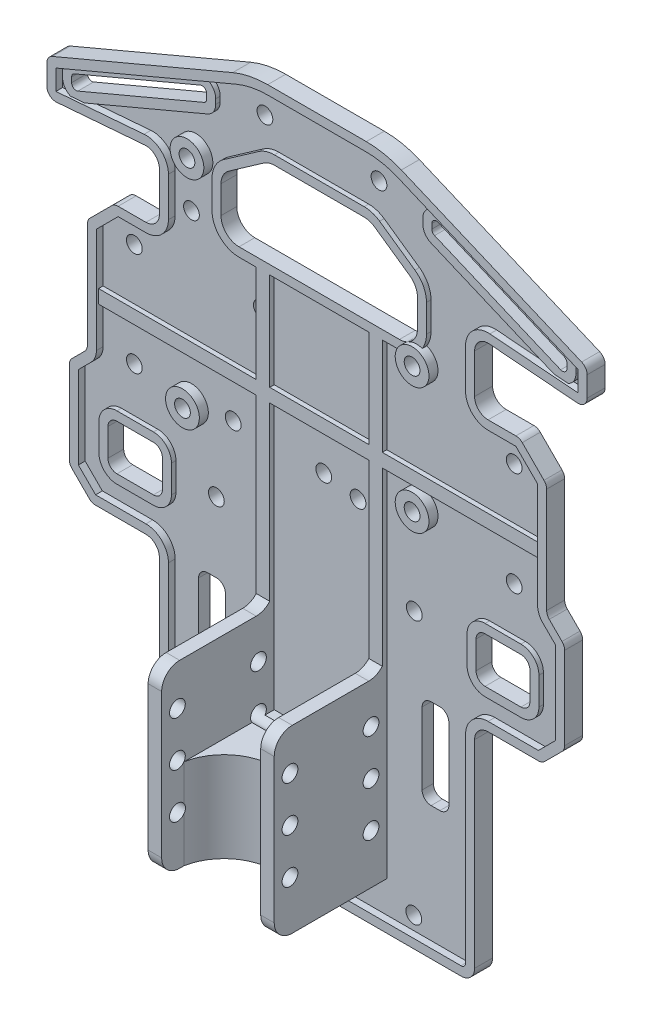
SolidWorks part; units mm, degrees
ref_plane "Front Plane" through (0, 0, 0) normal (0, 0, 1) x (1, 0, 0)
ref_plane "Top Plane" through (0, 0, 0) normal (0, 1, 0) x (1, 0, 0)
ref_plane "Right Plane" through (0, 0, 0) normal (1, 0, 0) x (0, 0, -1)
sketch "Sketch1" plane through (0, 0, 0) normal (0, 0, 1) x (1, 0, 0)
  line L1 (-55, 30) -> (-35, 30) construction
  line L2 (-55, 30) -> (-55, -30) construction
  line L3 (-55, -30) -> (-35, -30) construction
  line L4 (55, 30) -> (55, -30) construction
  line L5 (-55, 30) -> (55, -30) construction
  line L6 (-55, -30) -> (55, 30) construction
  line L8 (-35, 41.7504) -> (-35, 33)
  line L10 (35, 41.7504) -> (35, 33)
  line L11 (-35, 45) -> (35, 30) construction
  line L12 (-35, 30) -> (35, 45) construction
  line L13 (-60, 70) -> (60, 70) construction
  line L14 (-60, 70) -> (-60, 45) construction
  line L15 (-60, 45) -> (-35, 45) construction
  line L16 (60, 70) -> (60, 45) construction
  line L17 (-60, 70) -> (60, 45) construction
  line L18 (-60, 45) -> (60, 70) construction
  line L20 (0, 57.5) -> (0, 37.5) construction
  line L21 (32, -80) -> (-32, -80)
  line L22 (35, -77) -> (35, -33)
  line L24 (-35, -77) -> (-35, -33)
  line L25 (35, -80) -> (-35, -30) construction
  line L26 (35, -30) -> (-35, -80) construction
  line L27 (0, 37.5) -> (0, 0) construction
  line L28 (0, 0) -> (0, -55) construction
  line L29 (35, 45) -> (60, 45) construction
  line L30 (35, 30) -> (55, 30) construction
  line L31 (35, -30) -> (55, -30) construction
  line L32 (-35, -30) -> (35, -30) construction
  line L33 (35, 30) -> (-35, 30) construction
  line L34 (-35, 45) -> (35, 45) construction
  line L35 (-60, 45.1664) -> (-60, 49.6735)
  line L36 (-58.7779, 51.516) -> (-18.7303, 68.425)
  line L37 (-10.9508, 70) -> (10.9508, 70)
  line L38 (18.7303, 68.425) -> (58.7779, 51.516)
  line L39 (60, 49.6735) -> (60, 45.1664)
  line L40 (57.8405, 43.1728) -> (38.2392, 44.7409)
  line L41 (-38.2392, 44.7409) -> (-57.8405, 43.1728)
  line L42 (-60, 51) -> (60, 51) construction
  line L43 (60, 43) -> (-60, 43) construction
  line L44 (0, 57.5) -> (0, 70) construction
  line L45 (-38, -30) -> (-49.1716, -30)
  line L46 (-50.5858, -29.4142) -> (-54.4142, -25.5858)
  line L47 (-55, -24.1716) -> (-55, -5.8284)
  line L48 (-54.4142, -4.4142) -> (-51.5858, -1.5858)
  line L49 (-51, -0.1716) -> (-51, 23.1716)
  line L50 (-50.4142, 24.5858) -> (-45.5858, 29.4142)
  line L51 (-44.1716, 30) -> (-38, 30)
  line L52 (0, -55) -> (0, 55) construction
  line L53 (44.1716, 30) -> (38, 30)
  line L54 (50.4142, 24.5858) -> (45.5858, 29.4142)
  line L55 (51, -0.1716) -> (51, 23.1716)
  line L56 (54.4142, -4.4142) -> (51.5858, -1.5858)
  line L57 (55, -24.1716) -> (55, -5.8284)
  line L58 (50.5858, -29.4142) -> (54.4142, -25.5858)
  line L59 (38, -30) -> (49.1716, -30)
  line L60 (-55, 0) -> (55, 0) construction
  arc A0 (60, 45.1664) -> (57.8405, 43.1728) centre (58, 45.1664) cw
  arc A1 (58.7779, 51.516) -> (60, 49.6735) centre (58, 49.6735) cw
  arc A2 (-60, 45.1664) -> (-57.8405, 43.1728) centre (-58, 45.1664) ccw
  arc A3 (-60, 49.6735) -> (-58.7779, 51.516) centre (-58, 49.6735) cw
  arc A4 (10.9508, 70) -> (18.7303, 68.425) centre (10.9508, 50) cw
  arc A5 (-18.7303, 68.425) -> (-10.9508, 70) centre (-10.9508, 50) cw
  arc A6 (-45.5858, 29.4142) -> (-44.1716, 30) centre (-44.1716, 28) cw
  arc A7 (-51, 23.1716) -> (-50.4142, 24.5858) centre (-49, 23.1716) cw
  arc A8 (-51.5858, -1.5858) -> (-51, -0.1716) centre (-53, -0.1716) ccw
  arc A9 (-55, -5.8284) -> (-54.4142, -4.4142) centre (-53, -5.8284) cw
  arc A10 (-54.4142, -25.5858) -> (-55, -24.1716) centre (-53, -24.1716) cw
  arc A11 (-49.1716, -30) -> (-50.5858, -29.4142) centre (-49.1716, -28) cw
  arc A12 (45.5858, 29.4142) -> (44.1716, 30) centre (44.1716, 28) ccw
  arc A13 (51, 23.1716) -> (50.4142, 24.5858) centre (49, 23.1716) ccw
  arc A14 (51.5858, -1.5858) -> (51, -0.1716) centre (53, -0.1716) cw
  arc A15 (55, -5.8284) -> (54.4142, -4.4142) centre (53, -5.8284) ccw
  arc A16 (54.4142, -25.5858) -> (55, -24.1716) centre (53, -24.1716) ccw
  arc A17 (49.1716, -30) -> (50.5858, -29.4142) centre (49.1716, -28) ccw
  arc A18 (32, -80) -> (35, -77) centre (32, -77) ccw
  arc A19 (-32, -80) -> (-35, -77) centre (-32, -77) cw
  arc A20 (38.2392, 44.7409) -> (35, 41.7504) centre (38, 41.7504) ccw
  arc A21 (38, 30) -> (35, 33) centre (38, 33) cw
  arc A22 (-35, 33) -> (-38, 30) centre (-38, 33) cw
  arc A23 (-38.2392, 44.7409) -> (-35, 41.7504) centre (-38, 41.7504) cw
  arc A24 (35, -33) -> (38, -30) centre (38, -33) cw
  arc A25 (-38, -30) -> (-35, -33) centre (-38, -33) cw
  point P0 (0, 0)
  point P6 (0, 37.5)
  point P11 (0, 57.5)
  point P16 (0, -55)
  point P46 (15, 70)
  point P49 (-15, 70)
  point P58 (-45, 30)
  point P61 (-51, 24)
  point P64 (-51, -1)
  point P67 (-55, -5)
  point P70 (-55, -25)
  point P73 (-50, -30)
  dimension "D11" = 2
  dimension "D12" = 20
  dimension "D20" = 2
  dimension "D21" = 3
  dimension "D1" = 120
  dimension "D2" = 25
  dimension "D3" = 15
  dimension "D4" = 60
  dimension "D5" = 50
  dimension "D6" = 70
  dimension "D7" = 70
  dimension "D8" = 2
  dimension "D9" = 8
  dimension "D10" = 30
  dimension "D13" = 15
  dimension "D14" = 45
  dimension "D15" = 20
  dimension "D16" = 45
  dimension "D17" = 45
  dimension "D18" = 25
  dimension "D19" = 4
  dimension "D22" = 110
extrude "Boss-Extrude1" add sketch "Sketch1" along normal blind 2.5
sketch "Sketch14" plane through (0, 0, 2.5) normal (0, 0, 1) x (1, 0, 0)
  line L0 (-53.611, 47.1847) -> (-25.611, 59.0069)
  line L1 (-25, 59.9281) -> (-25, 61.0136)
  line L2 (-26.389, 61.9349) -> (-54.389, 50.1127)
  line L3 (-55, 49.1914) -> (-55, 48.1059)
  line L4 (-18.7303, 68.425) -> (-58.7779, 51.516) construction
  line L5 (0, -55) -> (0, 55) construction
  line L6 (55, 49.1914) -> (55, 48.1059)
  line L7 (26.389, 61.9349) -> (54.389, 50.1127)
  line L8 (25, 59.9281) -> (25, 61.0136)
  line L9 (53.611, 47.1847) -> (25.611, 59.0069)
  arc A0 (-25.611, 59.0069) -> (-25, 59.9281) centre (-26, 59.9281) ccw
  arc A1 (-25, 61.0136) -> (-26.389, 61.9349) centre (-26, 61.0136) ccw
  arc A2 (-53.611, 47.1847) -> (-55, 48.1059) centre (-54, 48.1059) cw
  arc A3 (-54.389, 50.1127) -> (-55, 49.1914) centre (-54, 49.1914) ccw
  arc A4 (54.389, 50.1127) -> (55, 49.1914) centre (54, 49.1914) cw
  arc A5 (53.611, 47.1847) -> (55, 48.1059) centre (54, 48.1059) ccw
  arc A6 (25, 61.0136) -> (26.389, 61.9349) centre (26, 61.0136) cw
  arc A7 (25.611, 59.0069) -> (25, 59.9281) centre (26, 59.9281) cw
  point P14 (-25, 60.4709)
  dimension "D1" = 1
  dimension "D2" = 3
  dimension "D3" = 30
  dimension "D4" = 3
  dimension "D5" = 25
extrude "Cut-Extrude6" cut sketch "Sketch14" against normal through all
sketch "Sketch17" plane through (0, 0, 2.5) normal (0, 0, 1) x (1, 0, 0)
  line L0 (21.6202, 4.389) -> (21.6202, 32.389) construction
  line L1 (-29.3798, 35.789) -> (-29.3798, -1.211) construction
  line L2 (-29.3798, -1.211) -> (7.6202, -1.211) construction
  line L3 (7.6202, -1.211) -> (7.6202, 35.789) construction
  line L4 (7.6202, 35.789) -> (-29.3798, 35.789) construction
  line L6 (24.6202, 4.389) -> (21.6202, 4.389) construction
  circle A0 centre (21.6202, 32.389) radius 1.75
  circle A1 centre (21.6202, 4.389) radius 1.75
  circle A2 centre (-29.3798, -1.211) radius 1.75
  circle A3 centre (-28.3798, 47.389) radius 1.75
  circle A4 centre (-29.3798, 35.789) radius 1.75
  circle A6 centre (7.6202, -1.211) radius 1.75
  dimension "D1" = 3.5
  dimension "D2" = 3.5
  dimension "D3" = 3.5
  dimension "D6" = 3.5
  dimension "D8" = 3.5
  dimension "D4" = 37
  dimension "D5" = 37
  dimension "D10" = 3
  dimension "D11" = 28
  dimension "D12" = 15
  dimension "D13" = 5.6
  dimension "D14" = 50
  dimension "D15" = 51
extrude "Cut-Extrude8" cut sketch "Sketch17" against normal through all both and the other way through all
ref_plane "Plane1" through (-35, -33, 2.5) normal (0, -1, 0) x (-1, 0, 0)
sketch "Sketch19" plane through (0, 0, 2.5) normal (0, 0, 1) x (1, 0, 0)
  line L0 (58, 45.1664) -> (58, 49.6735)
  line L1 (58, 49.6735) -> (17.9523, 66.5825)
  line L2 (10.9508, 68) -> (-10.9508, 68)
  line L3 (-17.9523, 66.5825) -> (-58, 49.6735)
  line L4 (-58, 49.6735) -> (-58, 45.1664)
  line L5 (-58, 45.1664) -> (-38.3987, 46.7345)
  line L6 (-33, 41.7504) -> (-33, 33)
  line L7 (-38, 28) -> (-44.1716, 28)
  line L8 (-44.1716, 28) -> (-49, 23.1716)
  line L9 (-49, 23.1716) -> (-49, -0.1716)
  line L10 (-50.1716, -3) -> (-53, -5.8284)
  line L11 (-53, -5.8284) -> (-53, -24.1716)
  line L12 (-53, -24.1716) -> (-49.1716, -28)
  line L13 (-49.1716, -28) -> (-38, -28)
  line L14 (-33, -33) -> (-33, -77)
  line L15 (-32, -78) -> (32, -78)
  line L16 (33, -77) -> (33, -33)
  line L17 (38, -28) -> (49.1716, -28)
  line L18 (49.1716, -28) -> (53, -24.1716)
  line L19 (53, -24.1716) -> (53, -5.8284)
  line L20 (53, -5.8284) -> (50.1716, -3)
  line L21 (49, -0.1716) -> (49, 23.1716)
  line L22 (49, 23.1716) -> (44.1716, 28)
  line L23 (44.1716, 28) -> (38, 28)
  line L24 (33, 33) -> (33, 41.7504)
  line L25 (38.3987, 46.7345) -> (58, 45.1664)
  line L26 (60, 45.1664) -> (60, 49.6735)
  line L27 (58.7779, 51.516) -> (18.7303, 68.425)
  line L28 (10.9508, 70) -> (-10.9508, 70)
  line L29 (-18.7303, 68.425) -> (-58.7779, 51.516)
  line L30 (-60, 49.6735) -> (-60, 45.1664)
  line L31 (-57.8405, 43.1728) -> (-38.2392, 44.7409)
  line L32 (-35, 41.7504) -> (-35, 33)
  line L33 (-38, 30) -> (-44.1716, 30)
  line L34 (-45.5858, 29.4142) -> (-50.4142, 24.5858)
  line L35 (-51, 23.1716) -> (-51, -0.1716)
  line L36 (-51.5858, -1.5858) -> (-54.4142, -4.4142)
  line L37 (-55, -5.8284) -> (-55, -24.1716)
  line L38 (-54.4142, -25.5858) -> (-50.5858, -29.4142)
  line L39 (-49.1716, -30) -> (-38, -30)
  line L40 (-35, -33) -> (-35, -77)
  line L41 (-32, -80) -> (32, -80)
  line L42 (35, -77) -> (35, -33)
  line L43 (38, -30) -> (49.1716, -30)
  line L44 (50.5858, -29.4142) -> (54.4142, -25.5858)
  line L45 (55, -24.1716) -> (55, -5.8284)
  line L46 (54.4142, -4.4142) -> (51.5858, -1.5858)
  line L47 (51, -0.1716) -> (51, 23.1716)
  line L48 (50.4142, 24.5858) -> (45.5858, 29.4142)
  line L49 (44.1716, 30) -> (38, 30)
  line L50 (35, 33) -> (35, 41.7504)
  line L51 (38.2392, 44.7409) -> (57.8405, 43.1728)
  line L52 (60, 45.1664) -> (60, 49.6735)
  line L53 (58.7779, 51.516) -> (18.7303, 68.425)
  line L54 (10.9508, 70) -> (-10.9508, 70)
  line L55 (-18.7303, 68.425) -> (-58.7779, 51.516)
  line L56 (-60, 49.6735) -> (-60, 45.1664)
  line L57 (-57.8405, 43.1728) -> (-38.2392, 44.7409)
  line L58 (-35, 41.7504) -> (-35, 33)
  line L59 (-38, 30) -> (-44.1716, 30)
  line L60 (-45.5858, 29.4142) -> (-50.4142, 24.5858)
  line L61 (-51, 23.1716) -> (-51, -0.1716)
  line L62 (-51.5858, -1.5858) -> (-54.4142, -4.4142)
  line L63 (-55, -5.8284) -> (-55, -24.1716)
  line L64 (-54.4142, -25.5858) -> (-50.5858, -29.4142)
  line L65 (-49.1716, -30) -> (-38, -30)
  line L66 (-35, -33) -> (-35, -77)
  line L67 (-32, -80) -> (32, -80)
  line L68 (35, -77) -> (35, -33)
  line L69 (38, -30) -> (49.1716, -30)
  line L70 (50.5858, -29.4142) -> (54.4142, -25.5858)
  line L71 (55, -24.1716) -> (55, -5.8284)
  line L72 (54.4142, -4.4142) -> (51.5858, -1.5858)
  line L73 (51, -0.1716) -> (51, 23.1716)
  line L74 (50.4142, 24.5858) -> (45.5858, 29.4142)
  line L75 (44.1716, 30) -> (38, 30)
  line L76 (35, 33) -> (35, 41.7504)
  line L77 (38.2392, 44.7409) -> (57.8405, 43.1728)
  arc A0 (58, 49.6735) -> (58, 49.6735) centre (58, 49.6735) ccw
  arc A1 (17.9523, 66.5825) -> (10.9508, 68) centre (10.9508, 50) ccw
  arc A2 (-10.9508, 68) -> (-17.9523, 66.5825) centre (-10.9508, 50) ccw
  arc A3 (-58, 49.6735) -> (-58, 49.6735) centre (-58, 49.6735) ccw
  arc A4 (-58, 45.1664) -> (-58, 45.1664) centre (-58, 45.1664) ccw
  arc A5 (-33, 41.7504) -> (-38.3987, 46.7345) centre (-38, 41.7504) ccw
  arc A6 (-38, 28) -> (-33, 33) centre (-38, 33) ccw
  arc A7 (-44.1716, 28) -> (-44.1716, 28) centre (-44.1716, 28) ccw
  arc A8 (-49, 23.1716) -> (-49, 23.1716) centre (-49, 23.1716) ccw
  arc A9 (-50.1716, -3) -> (-49, -0.1716) centre (-53, -0.1716) ccw
  arc A10 (-53, -5.8284) -> (-53, -5.8284) centre (-53, -5.8284) ccw
  arc A11 (-53, -24.1716) -> (-53, -24.1716) centre (-53, -24.1716) ccw
  arc A12 (-49.1716, -28) -> (-49.1716, -28) centre (-49.1716, -28) ccw
  arc A13 (-33, -33) -> (-38, -28) centre (-38, -33) ccw
  arc A14 (-33, -77) -> (-32, -78) centre (-32, -77) ccw
  arc A15 (32, -78) -> (33, -77) centre (32, -77) ccw
  arc A16 (38, -28) -> (33, -33) centre (38, -33) ccw
  arc A17 (49.1716, -28) -> (49.1716, -28) centre (49.1716, -28) ccw
  arc A18 (53, -24.1716) -> (53, -24.1716) centre (53, -24.1716) ccw
  arc A19 (53, -5.8284) -> (53, -5.8284) centre (53, -5.8284) ccw
  arc A20 (49, -0.1716) -> (50.1716, -3) centre (53, -0.1716) ccw
  arc A21 (49, 23.1716) -> (49, 23.1716) centre (49, 23.1716) ccw
  arc A22 (44.1716, 28) -> (44.1716, 28) centre (44.1716, 28) ccw
  arc A23 (33, 33) -> (38, 28) centre (38, 33) ccw
  arc A24 (38.3987, 46.7345) -> (33, 41.7504) centre (38, 41.7504) ccw
  arc A25 (58, 45.1664) -> (58, 45.1664) centre (58, 45.1664) ccw
  arc A26 (57.8405, 43.1728) -> (60, 45.1664) centre (58, 45.1664) ccw
  arc A27 (60, 49.6735) -> (58.7779, 51.516) centre (58, 49.6735) ccw
  arc A28 (18.7303, 68.425) -> (10.9508, 70) centre (10.9508, 50) ccw
  arc A29 (-10.9508, 70) -> (-18.7303, 68.425) centre (-10.9508, 50) ccw
  arc A30 (-58.7779, 51.516) -> (-60, 49.6735) centre (-58, 49.6735) ccw
  arc A31 (-60, 45.1664) -> (-57.8405, 43.1728) centre (-58, 45.1664) ccw
  arc A32 (-35, 41.7504) -> (-38.2392, 44.7409) centre (-38, 41.7504) ccw
  arc A33 (-38, 30) -> (-35, 33) centre (-38, 33) ccw
  arc A34 (-44.1716, 30) -> (-45.5858, 29.4142) centre (-44.1716, 28) ccw
  arc A35 (-50.4142, 24.5858) -> (-51, 23.1716) centre (-49, 23.1716) ccw
  arc A36 (-51.5858, -1.5858) -> (-51, -0.1716) centre (-53, -0.1716) ccw
  arc A37 (-54.4142, -4.4142) -> (-55, -5.8284) centre (-53, -5.8284) ccw
  arc A38 (-55, -24.1716) -> (-54.4142, -25.5858) centre (-53, -24.1716) ccw
  arc A39 (-50.5858, -29.4142) -> (-49.1716, -30) centre (-49.1716, -28) ccw
  arc A40 (-35, -33) -> (-38, -30) centre (-38, -33) ccw
  arc A41 (-35, -77) -> (-32, -80) centre (-32, -77) ccw
  arc A42 (32, -80) -> (35, -77) centre (32, -77) ccw
  arc A43 (38, -30) -> (35, -33) centre (38, -33) ccw
  arc A44 (49.1716, -30) -> (50.5858, -29.4142) centre (49.1716, -28) ccw
  arc A45 (54.4142, -25.5858) -> (55, -24.1716) centre (53, -24.1716) ccw
  arc A46 (55, -5.8284) -> (54.4142, -4.4142) centre (53, -5.8284) ccw
  arc A47 (51, -0.1716) -> (51.5858, -1.5858) centre (53, -0.1716) ccw
  arc A48 (51, 23.1716) -> (50.4142, 24.5858) centre (49, 23.1716) ccw
  arc A49 (45.5858, 29.4142) -> (44.1716, 30) centre (44.1716, 28) ccw
  arc A50 (35, 33) -> (38, 30) centre (38, 33) ccw
  arc A51 (38.2392, 44.7409) -> (35, 41.7504) centre (38, 41.7504) ccw
  arc A52 (57.8405, 43.1728) -> (60, 45.1664) centre (58, 45.1664) ccw
  arc A53 (60, 49.6735) -> (58.7779, 51.516) centre (58, 49.6735) ccw
  arc A54 (18.7303, 68.425) -> (10.9508, 70) centre (10.9508, 50) ccw
  arc A55 (-10.9508, 70) -> (-18.7303, 68.425) centre (-10.9508, 50) ccw
  arc A56 (-58.7779, 51.516) -> (-60, 49.6735) centre (-58, 49.6735) ccw
  arc A57 (-60, 45.1664) -> (-57.8405, 43.1728) centre (-58, 45.1664) ccw
  arc A58 (-35, 41.7504) -> (-38.2392, 44.7409) centre (-38, 41.7504) ccw
  arc A59 (-38, 30) -> (-35, 33) centre (-38, 33) ccw
  arc A60 (-44.1716, 30) -> (-45.5858, 29.4142) centre (-44.1716, 28) ccw
  arc A61 (-50.4142, 24.5858) -> (-51, 23.1716) centre (-49, 23.1716) ccw
  arc A62 (-51.5858, -1.5858) -> (-51, -0.1716) centre (-53, -0.1716) ccw
  arc A63 (-54.4142, -4.4142) -> (-55, -5.8284) centre (-53, -5.8284) ccw
  arc A64 (-55, -24.1716) -> (-54.4142, -25.5858) centre (-53, -24.1716) ccw
  arc A65 (-50.5858, -29.4142) -> (-49.1716, -30) centre (-49.1716, -28) ccw
  arc A66 (-35, -33) -> (-38, -30) centre (-38, -33) ccw
  arc A67 (-35, -77) -> (-32, -80) centre (-32, -77) ccw
  arc A68 (32, -80) -> (35, -77) centre (32, -77) ccw
  arc A69 (38, -30) -> (35, -33) centre (38, -33) ccw
  arc A70 (49.1716, -30) -> (50.5858, -29.4142) centre (49.1716, -28) ccw
  arc A71 (54.4142, -25.5858) -> (55, -24.1716) centre (53, -24.1716) ccw
  arc A72 (55, -5.8284) -> (54.4142, -4.4142) centre (53, -5.8284) ccw
  arc A73 (51, -0.1716) -> (51.5858, -1.5858) centre (53, -0.1716) ccw
  arc A74 (51, 23.1716) -> (50.4142, 24.5858) centre (49, 23.1716) ccw
  arc A75 (45.5858, 29.4142) -> (44.1716, 30) centre (44.1716, 28) ccw
  arc A76 (35, 33) -> (38, 30) centre (38, 33) ccw
  arc A77 (38.2392, 44.7409) -> (35, 41.7504) centre (38, 41.7504) ccw
  dimension "D1" = 0
  dimension "D2" = 2
extrude "Boss-Extrude2" add sketch "Sketch19" along normal blind 1.5
sketch "Sketch20" plane through (0, 0, 2.5) normal (0, 0, 1) x (1, 0, 0)
  line L0 (-20.1087, 48.5343) -> (-12.2683, 54.0191)
  line L2 (-21.8159, 45.2567) -> (-21.8159, 39.1272)
  line L3 (-17.8159, 35.1272) -> (17.8159, 35.1272)
  line L4 (21.8159, 45.2567) -> (21.8159, 39.1272)
  line L5 (-21.8159, 47.3401) -> (21.8159, 35.1272) construction
  line L6 (-21.8159, 35.1272) -> (21.8159, 47.3401) construction
  line L7 (-9.9754, 54.7415) -> (9.9754, 54.7415)
  line L8 (12.2683, 54.0191) -> (20.1087, 48.5343)
  line L9 (0, 0) -> (0, 41.2337) construction
  line L10 (0, 41.2337) -> (0, 54.7415) construction
  line L11 (-21.8451, -32.0477) -> (21.8451, -32.0477) construction
  line L16 (23.8451, -32.0477) -> (25.7855, -32.0477)
  line L17 (21.8451, -34.0477) -> (21.8451, -50.0121)
  line L18 (23.8451, -52.0121) -> (25.7855, -52.0121)
  line L19 (27.7855, -34.0477) -> (27.7855, -50.0121)
  line L20 (-25.7943, -32.0477) -> (-23.8451, -32.0477)
  line L21 (-27.7943, -34.0477) -> (-27.7943, -50.0121)
  line L22 (-25.7943, -52.0121) -> (-23.8451, -52.0121)
  line L23 (-21.8451, -34.0477) -> (-21.8451, -50.0121)
  line L24 (-21.8451, -52.0121) -> (27.7855, -52.0121) construction
  line L25 (0, -32.0477) -> (0, 0) construction
  line L26 (0, 0) -> (0, 9.9481) construction
  line L27 (-34.8257, -11.9839) -> (34.8257, -11.9839) construction
  line L28 (44.7902, -11.9839) -> (36.8257, -11.9839)
  line L29 (46.7902, -13.9839) -> (46.7902, -20.0923)
  line L30 (44.7902, -22.0923) -> (36.8257, -22.0923)
  line L31 (34.8257, -13.9839) -> (34.8257, -20.0923)
  line L32 (-36.8257, -11.9839) -> (-44.9308, -11.9839)
  line L33 (-34.8257, -13.9839) -> (-34.8257, -20.0923)
  line L34 (-36.8257, -22.0923) -> (-44.9308, -22.0923)
  line L35 (-46.9308, -13.9839) -> (-46.9308, -20.0923)
  line L36 (34.8257, -22.0923) -> (-34.8257, -22.0923) construction
  line L37 (0, -11.9839) -> (0, 0) construction
  line L38 (-32, -80) -> (32, -80) construction
  line L39 (-35, -33) -> (-35, -77) construction
  line L43 (0, 14.5554) -> (0, 0) construction
  arc A0 (-20.1087, 48.5343) -> (-21.8159, 45.2567) centre (-17.8159, 45.2567) ccw
  arc A1 (-21.8159, 39.1272) -> (-17.8159, 35.1272) centre (-17.8159, 39.1272) ccw
  arc A2 (17.8159, 35.1272) -> (21.8159, 39.1272) centre (17.8159, 39.1272) ccw
  arc A3 (20.1087, 48.5343) -> (21.8159, 45.2567) centre (17.8159, 45.2567) cw
  arc A4 (9.9754, 54.7415) -> (12.2683, 54.0191) centre (9.9754, 50.7415) cw
  arc A5 (-12.2683, 54.0191) -> (-9.9754, 54.7415) centre (-9.9754, 50.7415) cw
  arc A6 (21.8451, -50.0121) -> (23.8451, -52.0121) centre (23.8451, -50.0121) ccw
  arc A7 (25.7855, -52.0121) -> (27.7855, -50.0121) centre (25.7855, -50.0121) ccw
  arc A8 (25.7855, -32.0477) -> (27.7855, -34.0477) centre (25.7855, -34.0477) cw
  arc A9 (23.8451, -32.0477) -> (21.8451, -34.0477) centre (23.8451, -34.0477) ccw
  arc A10 (-27.7943, -50.0121) -> (-25.7943, -52.0121) centre (-25.7943, -50.0121) ccw
  arc A11 (-23.8451, -52.0121) -> (-21.8451, -50.0121) centre (-23.8451, -50.0121) ccw
  arc A12 (-23.8451, -32.0477) -> (-21.8451, -34.0477) centre (-23.8451, -34.0477) cw
  arc A13 (-25.7943, -32.0477) -> (-27.7943, -34.0477) centre (-25.7943, -34.0477) ccw
  arc A18 (46.7902, -20.0923) -> (44.7902, -22.0923) centre (44.7902, -20.0923) cw
  arc A19 (44.7902, -11.9839) -> (46.7902, -13.9839) centre (44.7902, -13.9839) cw
  arc A20 (36.8257, -11.9839) -> (34.8257, -13.9839) centre (36.8257, -13.9839) ccw
  arc A21 (36.8257, -22.0923) -> (34.8257, -20.0923) centre (36.8257, -20.0923) cw
  arc A22 (-34.8257, -20.0923) -> (-36.8257, -22.0923) centre (-36.8257, -20.0923) cw
  arc A23 (-36.8257, -11.9839) -> (-34.8257, -13.9839) centre (-36.8257, -13.9839) cw
  arc A24 (-44.9308, -11.9839) -> (-46.9308, -13.9839) centre (-44.9308, -13.9839) ccw
  arc A25 (-44.9308, -22.0923) -> (-46.9308, -20.0923) centre (-44.9308, -20.0923) cw
  circle A26 centre (-42.0638, 22.9587) radius 1.75
  circle A27 centre (42.2976, 22.9587) radius 1.75
  circle A28 centre (42.2976, -0.1284) radius 1.75
  circle A29 centre (-42.0638, 0) radius 1.75
  circle A30 centre (-23.8451, -16.4765) radius 1.75
  circle A31 centre (20.1087, -16.4765) radius 1.75
  circle A32 centre (-20.1087, 0) radius 1.75
  circle A33 centre (-13.8601, 24.581) radius 1.75
  circle A34 centre (-13.0606, 62.3533) radius 1.75
  circle A35 centre (12.2683, 62.3533) radius 1.75
  circle A36 centre (0, 0) radius 1.75
  circle A37 centre (-25, -75) radius 1.75
  circle A38 centre (-10, -75) radius 1.75
  circle A39 centre (5, -75) radius 1.75
  circle A40 centre (20, -75) radius 1.75
  circle A47 centre (35, -75) radius 1.75 [skipped]
  circle A48 centre (50, -75) radius 1.75 [skipped]
  point P0 (0, 41.2337)
  dimension "D1" = 4
  dimension "D2" = 2
  dimension "D3" = 2
  dimension "D4" = 3.5
  dimension "D5" = 5
  dimension "D6" = 10
  dimension "D7" = 6
extrude "Cut-Extrude9" cut sketch "Sketch20" against normal through all
sketch "Sketch21" plane through (0, 0, 2.5) normal (0, 0, 1) x (1, 0, 0)
  line L1 (-14, -71) -> (-11, -71)
  line L2 (-14, -71) -> (-14, -31)
  line L3 (-14, -31) -> (-11, -31)
  line L4 (-11, -51) -> (-11, -31)
  line L5 (-11, -31) -> (11, -31) construction
  line L6 (14, -71) -> (11, -71)
  line L7 (14, -71) -> (14, -31)
  line L8 (14, -31) -> (11, -31)
  line L9 (11, -51) -> (11, -31)
  line L10 (-33, -33) -> (-33, -77) construction
  line L11 (33, -77) -> (33, -33) construction
  line L12 (-11, -51) -> (11, -51)
  line L13 (-11, -71) -> (11, -71)
  line L14 (-32, -78) -> (32, -78) construction
  dimension "D1" = 19
  dimension "D2" = 19
  dimension "D3" = 3
  dimension "D4" = 3
  dimension "D5" = 40
  dimension "D6" = 20
  dimension "D7" = 7
extrude "Boss-Extrude3" add sketch "Sketch21" along normal blind 25
sketch "Sketch22" plane through (0, -71, 0) normal (0, -1, 0) x (1, 0, 0)
  line L0 (-14, 27.5) -> (14, 27.5) construction
  line L2 (-11, 22.5) -> (-11, 27.5)
  line L3 (-11, 27.5) -> (11, 27.5)
  line L4 (11, 27.5) -> (11, 22.5)
  line L5 (-14, 27.5) -> (-14, 2.5) construction
  line L6 (14, 27.5) -> (14, 2.5) construction
  line L7 (-11, 22.5) -> (11, 22.5) construction
  arc A0 (-11, 22.5) -> (11, 22.5) centre (0, 24.6283) ccw
  dimension "D1" = 3
  dimension "D2" = 3
  dimension "D3" = 5
extrude "Cut-Extrude10" cut sketch "Sketch22" against normal blind 33
sketch "Sketch23" plane through (-14, 0, 0) normal (-1, 0, 0) x (0, 0, 1)
  line L0 (6, -40) -> (24, -40) construction
  line L1 (15, -31) -> (15, -40) construction
  line L2 (27.5, -31) -> (2.5, -31) construction
  line L3 (4, -80) -> (0, -80) construction
  circle A0 centre (6, -40) radius 1.75
  circle A1 centre (24, -40) radius 1.75
  dimension "D2" = 3.5
  dimension "D1" = 18
  dimension "D3" = 40
extrude "Cut-Extrude11" cut sketch "Sketch23" against normal through all both and the other way through all
pattern_linear "LPattern1" count 3 spacing 10 along (0, -1, 0) of "Cut-Extrude11"
fillet "Fillet1" radius 4 6 edges at (-12.5, -71, 27.5) (12.5, -71, 27.5) (-12.5, -31, 27.5) (-12.5, -31, 2.5) (12.5, -31, 2.5) (12.5, -31, 27.5)
sketch "Sketch24" plane through (0, 0, 2.5) normal (0, 0, 1) x (1, 0, 0)
  line L0 (48.7902, -20.0923) -> (48.7902, -13.9839)
  line L1 (44.7902, -9.9839) -> (36.8257, -9.9839)
  line L2 (32.8257, -13.9839) -> (32.8257, -20.0923)
  line L3 (36.8257, -24.0923) -> (44.7902, -24.0923)
  line L4 (46.7902, -20.0923) -> (46.7902, -13.9839)
  line L5 (36.8257, -22.0923) -> (44.7902, -22.0923)
  line L6 (34.8257, -13.9839) -> (34.8257, -20.0923)
  line L7 (44.7902, -11.9839) -> (36.8257, -11.9839)
  line L8 (46.7902, -20.0923) -> (46.7902, -13.9839)
  line L9 (36.8257, -22.0923) -> (44.7902, -22.0923)
  line L10 (34.8257, -13.9839) -> (34.8257, -20.0923)
  line L11 (44.7902, -11.9839) -> (36.8257, -11.9839)
  line L12 (-34.8257, -20.0923) -> (-34.8257, -13.9839)
  line L13 (-44.9308, -22.0923) -> (-36.8257, -22.0923)
  line L14 (-46.9308, -13.9839) -> (-46.9308, -20.0923)
  line L15 (-36.8257, -11.9839) -> (-44.9308, -11.9839)
  line L16 (-34.8257, -20.0923) -> (-34.8257, -13.9839)
  line L17 (-44.9308, -22.0923) -> (-36.8257, -22.0923)
  line L18 (-46.9308, -13.9839) -> (-46.9308, -20.0923)
  line L19 (-36.8257, -11.9839) -> (-44.9308, -11.9839)
  line L20 (-25, 59.9281) -> (-25, 61.0136)
  line L21 (-53.611, 47.1847) -> (-25.611, 59.0069)
  line L22 (-55, 49.1914) -> (-55, 48.1059)
  line L23 (-26.389, 61.9349) -> (-54.389, 50.1127)
  line L24 (-25, 59.9281) -> (-25, 61.0136)
  line L25 (-53.611, 47.1847) -> (-25.611, 59.0069)
  line L26 (-55, 49.1914) -> (-55, 48.1059)
  line L27 (-26.389, 61.9349) -> (-54.389, 50.1127)
  line L28 (54.389, 50.1127) -> (26.389, 61.9349)
  line L29 (55, 48.1059) -> (55, 49.1914)
  line L30 (25.611, 59.0069) -> (53.611, 47.1847)
  line L31 (25, 61.0136) -> (25, 59.9281)
  line L32 (54.389, 50.1127) -> (26.389, 61.9349)
  line L33 (55, 48.1059) -> (55, 49.1914)
  line L34 (25.611, 59.0069) -> (53.611, 47.1847)
  line L35 (25, 61.0136) -> (25, 59.9281)
  line L37 (-17.8159, 33.1272) -> (17.8159, 33.1272)
  line L39 (23.8159, 39.1272) -> (23.8159, 45.2567)
  line L40 (21.2551, 50.1732) -> (13.4147, 55.6579)
  line L41 (9.9754, 56.7415) -> (-9.9754, 56.7415)
  line L56 (-32.8257, -20.0923) -> (-32.8257, -13.9839)
  line L57 (-36.8257, -9.9839) -> (-44.9308, -9.9839)
  line L58 (-48.9308, -13.9839) -> (-48.9308, -20.0923)
  line L59 (-44.9308, -24.0923) -> (-36.8257, -24.0923)
  line L60 (-23, 59.9281) -> (-23, 61.0136)
  line L61 (-27.1669, 63.7774) -> (-55.1669, 51.9552)
  line L62 (-57, 49.1914) -> (-57, 48.1059)
  line L63 (-52.8331, 45.3422) -> (-24.8331, 57.1644)
  line L64 (55.1669, 51.9552) -> (27.1669, 63.7774)
  line L65 (23, 61.0136) -> (23, 59.9281)
  line L66 (24.8331, 57.1644) -> (52.8331, 45.3422)
  line L67 (57, 48.1059) -> (57, 49.1914)
  line L94 (-13.4147, 55.6579) -> (-21.2551, 50.1732)
  line L95 (-23.8159, 45.2567) -> (-23.8159, 39.1272)
  line L96 (-21.8159, 45.2567) -> (-21.8159, 39.1272)
  line L97 (-12.2683, 54.0191) -> (-20.1087, 48.5343)
  line L98 (9.9754, 54.7415) -> (-9.9754, 54.7415)
  line L99 (20.1087, 48.5343) -> (12.2683, 54.0191)
  line L100 (21.8159, 39.1272) -> (21.8159, 45.2567)
  line L101 (-17.8159, 35.1272) -> (17.8159, 35.1272)
  line L102 (-21.8159, 45.2567) -> (-21.8159, 39.1272)
  line L103 (-12.2683, 54.0191) -> (-20.1087, 48.5343)
  line L104 (9.9754, 54.7415) -> (-9.9754, 54.7415)
  line L105 (20.1087, 48.5343) -> (12.2683, 54.0191)
  line L106 (21.8159, 39.1272) -> (21.8159, 45.2567)
  line L107 (-17.8159, 35.1272) -> (17.8159, 35.1272)
  arc A0 (48.7902, -13.9839) -> (44.7902, -9.9839) centre (44.7902, -13.9839) ccw
  arc A1 (36.8257, -9.9839) -> (32.8257, -13.9839) centre (36.8257, -13.9839) ccw
  arc A2 (32.8257, -20.0923) -> (36.8257, -24.0923) centre (36.8257, -20.0923) ccw
  arc A3 (44.7902, -24.0923) -> (48.7902, -20.0923) centre (44.7902, -20.0923) ccw
  arc A4 (44.7902, -22.0923) -> (46.7902, -20.0923) centre (44.7902, -20.0923) ccw
  arc A5 (34.8257, -20.0923) -> (36.8257, -22.0923) centre (36.8257, -20.0923) ccw
  arc A6 (36.8257, -11.9839) -> (34.8257, -13.9839) centre (36.8257, -13.9839) ccw
  arc A7 (46.7902, -13.9839) -> (44.7902, -11.9839) centre (44.7902, -13.9839) ccw
  arc A8 (44.7902, -22.0923) -> (46.7902, -20.0923) centre (44.7902, -20.0923) ccw
  arc A9 (34.8257, -20.0923) -> (36.8257, -22.0923) centre (36.8257, -20.0923) ccw
  arc A10 (36.8257, -11.9839) -> (34.8257, -13.9839) centre (36.8257, -13.9839) ccw
  arc A11 (46.7902, -13.9839) -> (44.7902, -11.9839) centre (44.7902, -13.9839) ccw
  arc A12 (-36.8257, -22.0923) -> (-34.8257, -20.0923) centre (-36.8257, -20.0923) ccw
  arc A13 (-46.9308, -20.0923) -> (-44.9308, -22.0923) centre (-44.9308, -20.0923) ccw
  arc A14 (-44.9308, -11.9839) -> (-46.9308, -13.9839) centre (-44.9308, -13.9839) ccw
  arc A15 (-34.8257, -13.9839) -> (-36.8257, -11.9839) centre (-36.8257, -13.9839) ccw
  arc A16 (-36.8257, -22.0923) -> (-34.8257, -20.0923) centre (-36.8257, -20.0923) ccw
  arc A17 (-46.9308, -20.0923) -> (-44.9308, -22.0923) centre (-44.9308, -20.0923) ccw
  arc A18 (-44.9308, -11.9839) -> (-46.9308, -13.9839) centre (-44.9308, -13.9839) ccw
  arc A19 (-34.8257, -13.9839) -> (-36.8257, -11.9839) centre (-36.8257, -13.9839) ccw
  arc A20 (-25.611, 59.0069) -> (-25, 59.9281) centre (-26, 59.9281) ccw
  arc A21 (-55, 48.1059) -> (-53.611, 47.1847) centre (-54, 48.1059) ccw
  arc A22 (-54.389, 50.1127) -> (-55, 49.1914) centre (-54, 49.1914) ccw
  arc A23 (-25, 61.0136) -> (-26.389, 61.9349) centre (-26, 61.0136) ccw
  arc A24 (-25.611, 59.0069) -> (-25, 59.9281) centre (-26, 59.9281) ccw
  arc A25 (-55, 48.1059) -> (-53.611, 47.1847) centre (-54, 48.1059) ccw
  arc A26 (-54.389, 50.1127) -> (-55, 49.1914) centre (-54, 49.1914) ccw
  arc A27 (-25, 61.0136) -> (-26.389, 61.9349) centre (-26, 61.0136) ccw
  arc A28 (55, 49.1914) -> (54.389, 50.1127) centre (54, 49.1914) ccw
  arc A29 (53.611, 47.1847) -> (55, 48.1059) centre (54, 48.1059) ccw
  arc A30 (25, 59.9281) -> (25.611, 59.0069) centre (26, 59.9281) ccw
  arc A31 (26.389, 61.9349) -> (25, 61.0136) centre (26, 61.0136) ccw
  arc A32 (55, 49.1914) -> (54.389, 50.1127) centre (54, 49.1914) ccw
  arc A33 (53.611, 47.1847) -> (55, 48.1059) centre (54, 48.1059) ccw
  arc A34 (25, 59.9281) -> (25.611, 59.0069) centre (26, 59.9281) ccw
  arc A35 (26.389, 61.9349) -> (25, 61.0136) centre (26, 61.0136) ccw
  arc A56 (-32.8257, -13.9839) -> (-36.8257, -9.9839) centre (-36.8257, -13.9839) ccw
  arc A57 (-44.9308, -9.9839) -> (-48.9308, -13.9839) centre (-44.9308, -13.9839) ccw
  arc A58 (-48.9308, -20.0923) -> (-44.9308, -24.0923) centre (-44.9308, -20.0923) ccw
  arc A59 (-36.8257, -24.0923) -> (-32.8257, -20.0923) centre (-36.8257, -20.0923) ccw
  arc A60 (-23, 61.0136) -> (-27.1669, 63.7774) centre (-26, 61.0136) ccw
  arc A61 (-55.1669, 51.9552) -> (-57, 49.1914) centre (-54, 49.1914) ccw
  arc A62 (-57, 48.1059) -> (-52.8331, 45.3422) centre (-54, 48.1059) ccw
  arc A63 (-24.8331, 57.1644) -> (-23, 59.9281) centre (-26, 59.9281) ccw
  arc A64 (27.1669, 63.7774) -> (23, 61.0136) centre (26, 61.0136) ccw
  arc A65 (23, 59.9281) -> (24.8331, 57.1644) centre (26, 59.9281) ccw
  arc A66 (52.8331, 45.3422) -> (57, 48.1059) centre (54, 48.1059) ccw
  arc A67 (57, 49.1914) -> (55.1669, 51.9552) centre (54, 49.1914) ccw
  arc A90 (17.8159, 33.1272) -> (23.8159, 39.1272) centre (17.8159, 39.1272) ccw
  arc A91 (23.8159, 45.2567) -> (21.2551, 50.1732) centre (17.8159, 45.2567) ccw
  arc A92 (13.4147, 55.6579) -> (9.9754, 56.7415) centre (9.9754, 50.7415) ccw
  arc A93 (-9.9754, 56.7415) -> (-13.4147, 55.6579) centre (-9.9754, 50.7415) ccw
  arc A113 (-21.2551, 50.1732) -> (-23.8159, 45.2567) centre (-17.8159, 45.2567) ccw
  arc A114 (-23.8159, 39.1272) -> (-17.8159, 33.1272) centre (-17.8159, 39.1272) ccw
  arc A115 (-20.1087, 48.5343) -> (-21.8159, 45.2567) centre (-17.8159, 45.2567) ccw
  arc A116 (-9.9754, 54.7415) -> (-12.2683, 54.0191) centre (-9.9754, 50.7415) ccw
  arc A117 (12.2683, 54.0191) -> (9.9754, 54.7415) centre (9.9754, 50.7415) ccw
  arc A118 (21.8159, 45.2567) -> (20.1087, 48.5343) centre (17.8159, 45.2567) ccw
  arc A119 (17.8159, 35.1272) -> (21.8159, 39.1272) centre (17.8159, 39.1272) ccw
  arc A120 (-21.8159, 39.1272) -> (-17.8159, 35.1272) centre (-17.8159, 39.1272) ccw
  arc A121 (-20.1087, 48.5343) -> (-21.8159, 45.2567) centre (-17.8159, 45.2567) ccw
  arc A122 (-9.9754, 54.7415) -> (-12.2683, 54.0191) centre (-9.9754, 50.7415) ccw
  arc A123 (12.2683, 54.0191) -> (9.9754, 54.7415) centre (9.9754, 50.7415) ccw
  arc A124 (21.8159, 45.2567) -> (20.1087, 48.5343) centre (17.8159, 45.2567) ccw
  arc A125 (17.8159, 35.1272) -> (21.8159, 39.1272) centre (17.8159, 39.1272) ccw
  arc A126 (-21.8159, 39.1272) -> (-17.8159, 35.1272) centre (-17.8159, 39.1272) ccw
  dimension "D1" = 0
  dimension "D2" = 0
  dimension "D3" = 0
  dimension "D4" = 0
  dimension "D7" = 2
  dimension "D8" = 0
  dimension "D9" = 2
extrude "Boss-Extrude4" add sketch "Sketch24" along normal blind 1
sketch "Sketch25" plane through (0, 0, 2.5) normal (0, 0, 1) x (1, 0, 0)
  circle A0 centre (21.6202, 32.389) radius 1.75
  circle A1 centre (21.6202, 4.389) radius 1.75
  circle A2 centre (21.6202, 4.389) radius 1.75
  circle A3 centre (-29.3798, -1.211) radius 1.75
  circle A4 centre (-29.3798, -1.211) radius 1.75
  circle A5 centre (-28.3798, 47.389) radius 1.75
  circle A6 centre (-28.3798, 47.389) radius 1.75
  circle A7 centre (21.6202, 32.389) radius 3.75
  circle A8 centre (-28.3798, 47.389) radius 3.75
  circle A9 centre (-29.3798, -1.211) radius 3.75
  circle A10 centre (21.6202, 4.389) radius 3.75
  dimension "D1" = 0
  dimension "D2" = 0
  dimension "D3" = 0
  dimension "D4" = 2
extrude "Boss-Extrude5" add sketch "Sketch25" along normal blind 2
sketch "Sketch26" plane through (0, 0, 2.5) normal (0, 0, 1) x (1, 0, 0)
  line L0 (-14, -27) -> (-14, -71) construction
  line L1 (-14, -35) -> (-11, -35)
  line L2 (-14, -35) -> (-14, 8.5034)
  line L3 (-14, 33.1272) -> (-11, 33.1272)
  line L4 (-11, -35) -> (-11, 8.5034)
  line L5 (-11, -35) -> (-14, -35) construction
  line L6 (-17.8159, 33.1272) -> (17.8159, 33.1272) construction
  line L7 (-11, -51) -> (-11, -27) construction
  line L8 (-11, -67) -> (-11, -35) construction
  line L9 (14, -67) -> (14, -35) construction
  line L10 (11, -35) -> (14, -35)
  line L11 (11, -35) -> (11, 8.5034)
  line L12 (11, 33.1272) -> (14, 33.1272)
  line L13 (14, -35) -> (14, 8.5034)
  line L14 (14, -71) -> (14, -27) construction
  line L15 (-49, 23.1716) -> (-49, -0.1716) construction
  line L16 (-49, 8.5034) -> (-14, 8.5034)
  line L17 (-49, 8.5034) -> (-49, 11.5034)
  line L18 (-49, 11.5034) -> (-14, 11.5034)
  line L19 (49, 8.5034) -> (49, 11.5034)
  line L20 (49, -0.1716) -> (49, 23.1716) construction
  line L21 (-11, 11.5034) -> (11, 11.5034)
  line L22 (-11, 8.5034) -> (11, 8.5034)
  line L23 (-14, 11.5034) -> (-14, 33.1272)
  line L24 (-11, 11.5034) -> (-11, 33.1272)
  line L25 (14, 11.5034) -> (49, 11.5034)
  line L26 (14, 8.5034) -> (49, 8.5034)
  line L27 (11, 11.5034) -> (11, 33.1272)
  line L28 (14, 11.5034) -> (14, 33.1272)
  dimension "D1" = 3
extrude "Boss-Extrude6" add sketch "Sketch26" along normal blind 1
